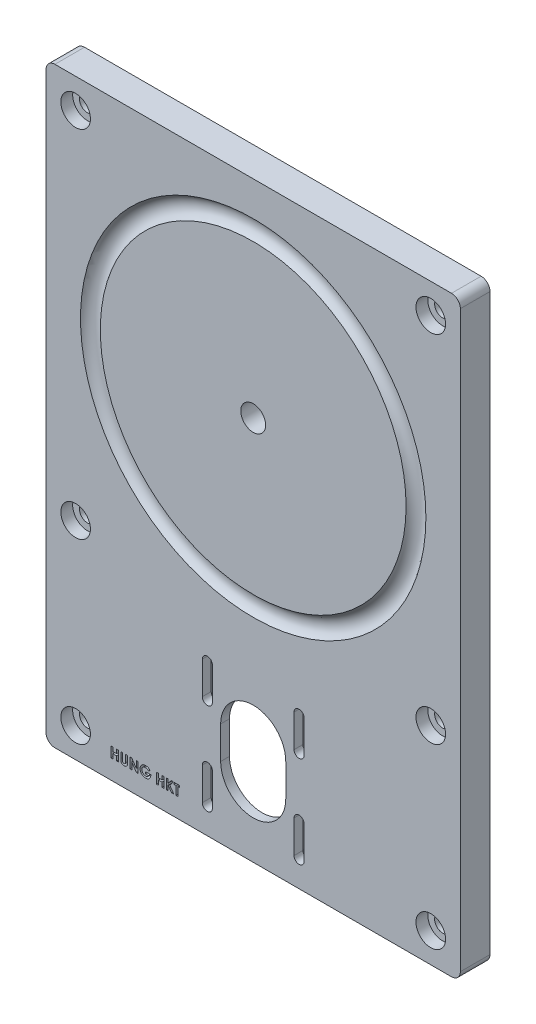
SolidWorks part; units mm, degrees
ref_plane "Front Plane" through (0, 0, 0) normal (0, 0, 1) x (1, 0, 0)
ref_plane "Top Plane" through (0, 0, 0) normal (0, 1, 0) x (1, 0, 0)
ref_plane "Right Plane" through (0, 0, 0) normal (1, 0, 0) x (0, 0, -1)
sketch "Sketch1" plane through (0, 0, 0) normal (0, 1, 0) x (1, 0, 0)
  line L0 (0, 0) -> (0, 10)
  line L1 (0, 10) -> (65, 10)
  line L7 (65, 0) -> (58.3466, 0)
  line L8 (0, 0) -> (51.6534, 0)
  line L9 (51.6534, 0) -> (0, 0)
  line L10 (65, 10) -> (65, 0)
  arc A0 (58.3466, 0) -> (51.6534, 0) centre (55, -1.8) ccw
revolve "Revolve1" add sketch "Sketch1" angle 360 about L0
sketch "Sketch3" plane through (0, 0, -10) normal (0, 0, -1) x (-1, 0, 0)
  circle A0 centre (0, 0) radius 4.2
extrude "Cut-Extrude1" cut sketch "Sketch3" against normal blind 38
sketch "Sketch4" plane through (0, 0, 0) normal (0, 0, 1) x (1, 0, 0)
  line L0 (-70, 0) -> (-70, 70)
  line L1 (-70, 70) -> (70, 70)
  line L2 (70, 70) -> (70, -130)
  line L3 (70, -130) -> (-70, -130)
  line L4 (-70, -130) -> (-70, 0)
  line L19 (-17.2, -90.1407) -> (-17.2, -79.1407)
  line L20 (-13.8, -79.1407) -> (-13.8, -90.1407)
  line L21 (-17.2, -110.1407) -> (-17.2, -121.1407)
  line L22 (13.8, -79.1407) -> (13.8, -90.1407)
  line L23 (17.2, -79.1407) -> (17.2, -90.1407)
  line L24 (-11, -95) -> (-11, -106)
  line L25 (11, -95) -> (11, -106)
  line L26 (13.8, -110.1407) -> (13.8, -121.1407)
  line L27 (17.2, -110.1407) -> (17.2, -121.1407)
  line L28 (-13.8, -110.1407) -> (-13.8, -121.1407)
  circle A0 centre (0, 0) radius 65
  circle A1 centre (-60, 60) radius 2.7
  circle A2 centre (60, 60) radius 2.7
  circle A3 centre (-60, -60) radius 2.7
  circle A4 centre (60, -60) radius 2.7
  circle A5 centre (60, -120) radius 2.7
  circle A6 centre (-60, -120) radius 2.7
  arc A7 (11, -95) -> (-11, -95) centre (0, -95) ccw
  arc A8 (-11, -106) -> (11, -106) centre (0, -106) ccw
  arc A9 (-13.8, -79.1407) -> (-17.2, -79.1407) centre (-15.5, -79.1407) ccw
  arc A10 (17.2, -79.1407) -> (13.8, -79.1407) centre (15.5, -79.1407) ccw
  arc A11 (-17.2, -90.1407) -> (-13.8, -90.1407) centre (-15.5, -90.1407) ccw
  arc A12 (13.8, -90.1407) -> (17.2, -90.1407) centre (15.5, -90.1407) ccw
  arc A13 (-13.8, -110.1407) -> (-17.2, -110.1407) centre (-15.5, -110.1407) ccw
  arc A14 (17.2, -110.1407) -> (13.8, -110.1407) centre (15.5, -110.1407) ccw
  arc A15 (-17.2, -121.1407) -> (-13.8, -121.1407) centre (-15.5, -121.1407) ccw
  arc A16 (13.8, -121.1407) -> (17.2, -121.1407) centre (15.5, -121.1407) ccw
extrude "Boss-Extrude2" add sketch "Sketch4" against normal blind 10
sketch "Sketch5" plane through (0, 0, -10) normal (0, 0, -1) x (-1, 0, 0)
  line L3 (21.5359, -84.5) -> (21.5359, -72.9996)
  line L4 (21.5359, -72.9996) -> (-21.5359, -72.9996)
  line L5 (-21.5359, -84.5) -> (-21.5359, -72.9996)
  line L8 (-21.5359, -127.5) -> (21.5359, -127.5)
  line L9 (-21.5359, -127.5) -> (-21.5359, -84.5)
  line L11 (21.5359, -127.5) -> (21.5359, -84.5)
  point P8 (0, -106)
extrude "Cut-Extrude2" cut sketch "Sketch5" against normal blind 7
fillet "Fillet1" radius 3 4 edges at (70, -130, -5) (-70, -130, -5) (70, 70, -5) (-70, 70, -5)
sketch "Sketch6" plane through (0, 0, 0) normal (0, 0, 1) x (1, 0, 0)
  circle A0 centre (-60, 60) radius 5
  circle A1 centre (60, 60) radius 5
  circle A2 centre (-60, -60) radius 5
  circle A3 centre (60, -60) radius 5
  circle A4 centre (-60, -120) radius 5
  circle A5 centre (60, -120) radius 5
  text T0 "<b>HUNG HKT </b>"
extrude "Cut-Extrude3" cut sketch "Sketch6" against normal blind 4
